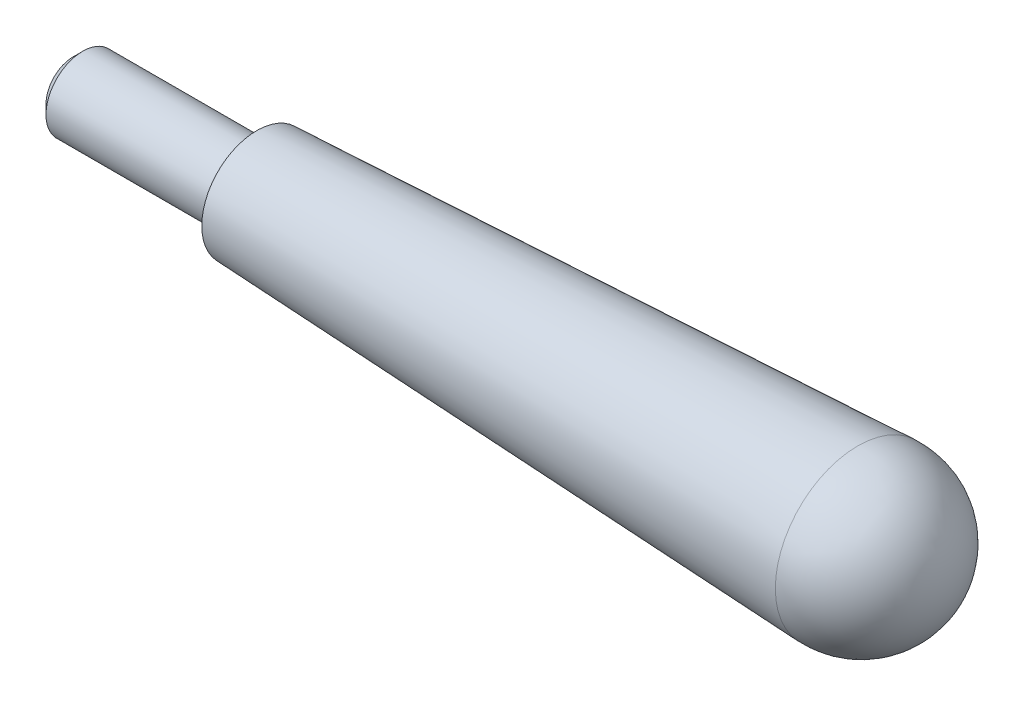
SolidWorks part; units mm, degrees
ref_plane "Спереди" through (0, 0, 0) normal (0, 0, 1) x (1, 0, 0)
ref_plane "Сверху" through (0, 0, 0) normal (0, 1, 0) x (1, 0, 0)
ref_plane "Справа" through (0, 0, 0) normal (1, 0, 0) x (0, 0, -1)
sketch "Эскиз1" plane through (0, 0, 0) normal (0, 0, 1) x (1, 0, 0)
  line L0 (0, 0) -> (0, 4)
  line L1 (0, 4) -> (20, 4)
  line L2 (0, 0) -> (86, 0)
  line L3 (20, 4) -> (20, 6)
  line L4 (20, 6) -> (85.5901, 8.9907)
  line L5 (86, 0) -> (95, 0)
  line L6 (0, 0) -> (95, 0) construction
  arc A0 (95, 0) -> (85.5901, 8.9907) centre (86, 0) ccw
  dimension "D1" = 9
  dimension "D2" = 95
  dimension "D3" = 6
  dimension "D4" = 4
revolve "Повернуть1" add sketch "Эскиз1" angle 360 about L6
chamfer "Фаска1" distance 1 angle 45 1 edges at (0, 0, 4)
